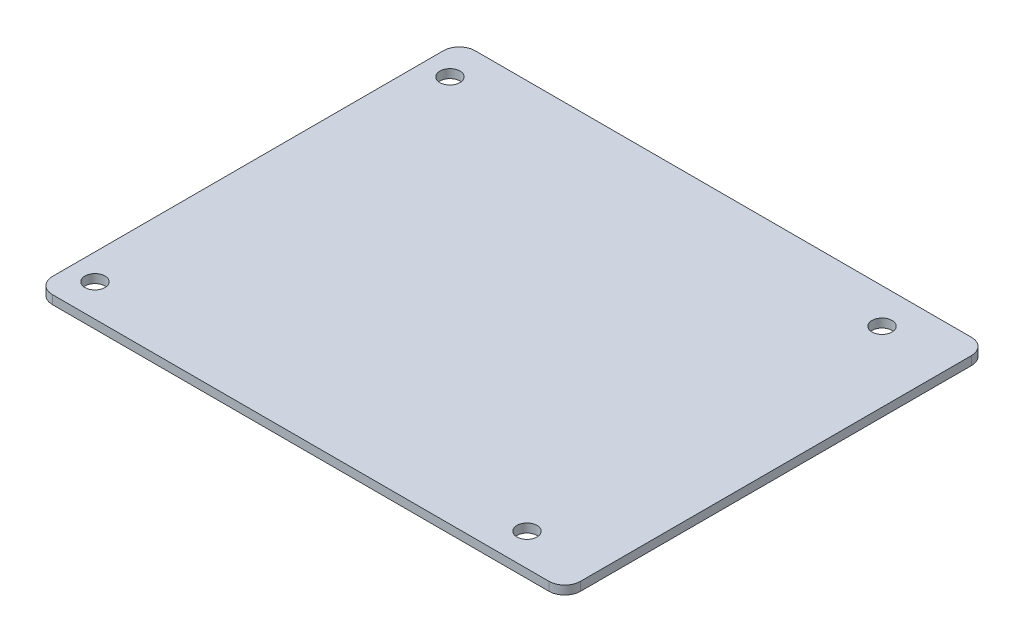
SolidWorks part; units mm, degrees
ref_plane "Front Plane" through (0, 0, 0) normal (0, 0, 1) x (1, 0, 0)
ref_plane "Top Plane" through (0, 0, 0) normal (0, 1, 0) x (1, 0, 0)
ref_plane "Right Plane" through (0, 0, 0) normal (1, 0, 0) x (0, 0, -1)
sketch "Sketch1" plane through (0, 0, 0) normal (0, 1, 0) x (1, 0, 0)
  line L1 (50.06, -40.06) -> (-50.06, -40.06)
  line L2 (50.06, -40.06) -> (50.06, 40.06)
  line L3 (50.06, 40.06) -> (-50.06, 40.06)
  line L4 (-50.06, -40.06) -> (-50.06, 40.06)
  line L5 (50.06, -40.06) -> (-50.06, 40.06) construction
  line L6 (50.06, 40.06) -> (-50.06, -40.06) construction
  point P0 (0, 0)
  dimension "D1" = 100.12
  dimension "D2" = 80.12
extrude "Boss-Extrude1" add sketch "Sketch1" along normal mid plane 1.65
fillet "Fillet1" radius 3 4 edges at (-50.06, 0, -40.06) (50.06, 0, -40.06) (50.06, 0, 40.06) (-50.06, 0, 40.06)
sketch "Sketch2" plane through (0, 0.825, 0) normal (0, 1, 0) x (1, 0, 0)
  line L0 (-50.06, 37.06) -> (-50.06, -37.06) construction
  line L2 (47.06, 40.06) -> (-47.06, 40.06) construction
  line L4 (36.76, -33.9175) -> (-45.155, -33.9175) construction
  line L5 (36.76, -33.9175) -> (36.76, 33.3925) construction
  line L6 (36.76, 33.3925) -> (-45.155, 33.3925) construction
  line L7 (-45.155, -33.9175) -> (-45.155, 33.3925) construction
  line L8 (36.76, -33.9175) -> (-45.155, 33.3925) construction
  line L9 (36.76, 33.3925) -> (-45.155, -33.9175) construction
  circle A0 centre (-45.155, 33.3925) radius 1.905
  circle A1 centre (-45.155, -33.9175) radius 1.905
  circle A2 centre (36.76, -33.9175) radius 1.905
  circle A3 centre (36.76, 33.3925) radius 1.905
  point P8 (-47.06, 33.3925)
  point P11 (-45.155, 35.2975)
  point P16 (-4.1975, -0.2625)
  dimension "D1" = 3.81
  dimension "D2" = 3
  dimension "D3" = 4.7625
  dimension "D4" = 67.31
  dimension "D5" = 81.915
extrude "Cut-Extrude1" cut sketch "Sketch2" against normal up to next
